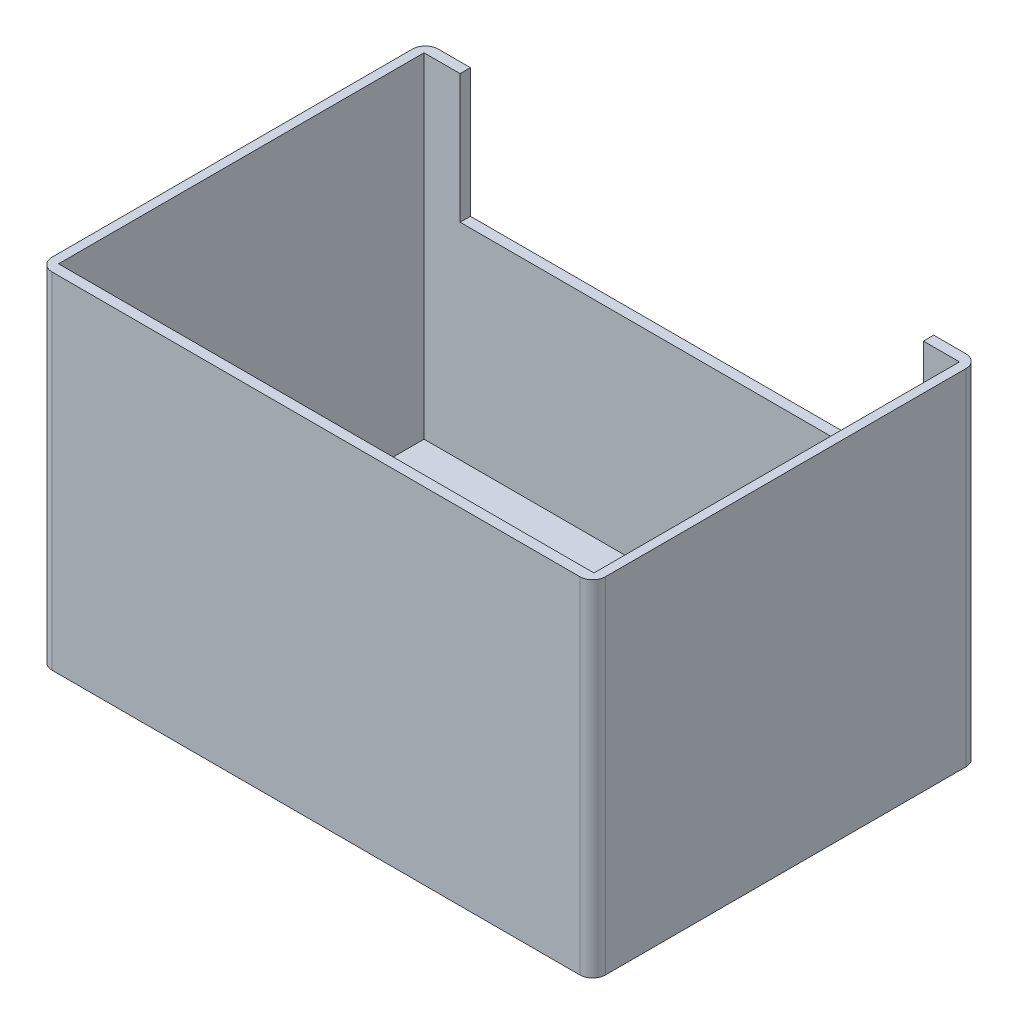
SolidWorks part; units mm, degrees
ref_plane "Front Plane" through (0, 0, 0) normal (0, 0, 1) x (1, 0, 0)
ref_plane "Top Plane" through (0, 0, 0) normal (0, 1, 0) x (1, 0, 0)
ref_plane "Right Plane" through (0, 0, 0) normal (1, 0, 0) x (0, 0, -1)
sketch "Sketch1" plane through (0, 0, 0) normal (0, 1, 0) x (1, 0, 0)
  line L1 (-107.5, 80) -> (107.5, 80)
  line L2 (-107.5, 80) -> (-107.5, -70)
  line L3 (-107.5, -70) -> (107.5, -70)
  line L4 (107.5, 80) -> (107.5, -70)
  dimension "D1" = 215
  dimension "D2" = 150
  dimension "D3" = 80
  dimension "D4" = 107.5
extrude "Boss-Extrude1" add sketch "Sketch1" along normal blind 4
sketch "Sketch2" plane through (0, 4, 0) normal (0, 1, 0) x (1, 0, 0)
  line L1 (-107.5, 80) -> (107.5, 80)
  line L2 (-107.5, 80) -> (-107.5, -70)
  line L3 (-107.5, -70) -> (107.5, -70)
  line L4 (107.5, 80) -> (107.5, -70)
  line L5 (-104, 76) -> (104, 76)
  line L6 (-104, 76) -> (-104, -66)
  line L7 (-104, -66) -> (104, -66)
  line L8 (104, 76) -> (104, -66)
  dimension "D1" = 208
  dimension "D2" = 142
  dimension "D3" = 4
  dimension "D4" = 3.5
extrude "Boss-Extrude2" add sketch "Sketch2" along normal blind 130
sketch "Sketch4" plane through (0, 0, -80) normal (0, 0, -1) x (-1, 0, 0)
  line L0 (-107.5, 134) -> (107.5, 134) construction
  line L1 (-90, 134) -> (90, 134)
  line L2 (-90, 134) -> (-90, 84)
  line L3 (-90, 84) -> (90, 84)
  line L4 (90, 134) -> (90, 84)
  dimension "D1" = 50
  dimension "D2" = 180
  dimension "D3" = 90
extrude "Cut-Extrude1" cut sketch "Sketch4" against normal blind 6
fillet "Fillet1" radius 5 1 edges at (-107.5, 67, -80)
fillet "Fillet2" radius 5 1 edges at (107.5, 67, -80)
fillet "Fillet3" radius 5 1 edges at (-107.5, 67, 70)
fillet "Fillet4" radius 5 1 edges at (107.5, 67, 70)
sketch "Sketch6" plane through (0, 0, 0) normal (0, -1, 0) x (-1, 0, 0)
  circle A0 centre (15, -20) radius 2.25
  circle A1 centre (-15, -40) radius 2.25
  circle A2 centre (15, 0) radius 2.25
  circle A3 centre (-15, -20) radius 2.25
  circle A4 centre (15, 20) radius 2.25
  circle A5 centre (-15, 20) radius 2.25
  circle A6 centre (15, -40) radius 2.25
  circle A7 centre (-15, 0) radius 2.25
  dimension "D1" = 4.5
  dimension "D2" = 4.5
  dimension "D3" = 4.5
  dimension "D4" = 4.5
  dimension "D5" = 4.5
  dimension "D6" = 4.5
  dimension "D7" = 20
  dimension "D8" = 20
  dimension "D9" = 0
  dimension "D10" = 0
  dimension "D11" = 4.5
  dimension "D12" = 0
  dimension "D13" = 0
  dimension "D14" = 4.5
  dimension "D15" = 20
  dimension "D16" = 20
  dimension "D17" = 20
  dimension "D18" = 20
  dimension "D19" = 20
  dimension "D20" = 20
  dimension "D21" = 15
  dimension "D22" = 15
extrude "Cut-Extrude2" cut sketch "Sketch6" against normal blind 6
